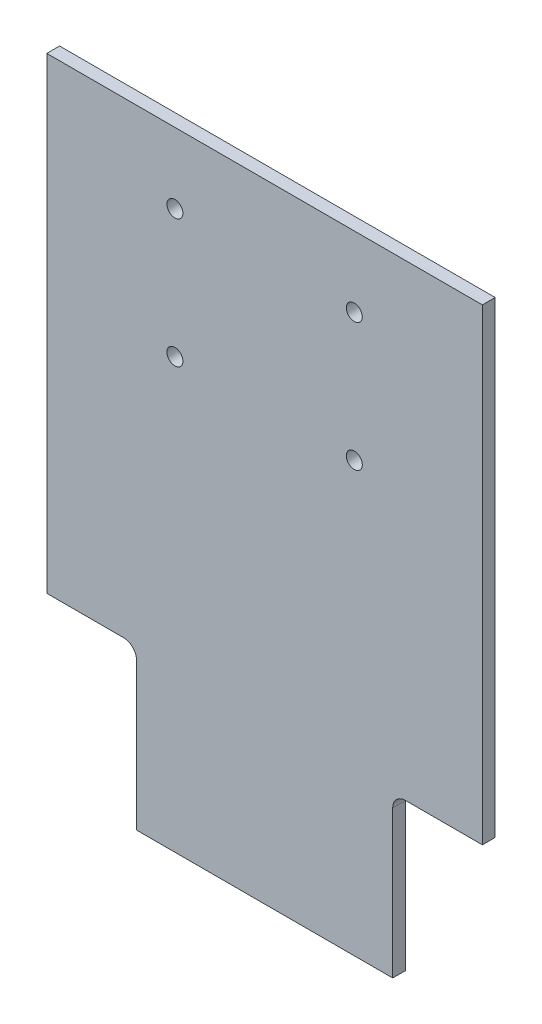
SolidWorks part; units mm, degrees
material "6063-T5"
ref_plane "前视基准面" through (0, 0, 0) normal (0, 0, 1) x (1, 0, 0)
ref_plane "上视基准面" through (0, 0, 0) normal (0, 1, 0) x (1, 0, 0)
ref_plane "右视基准面" through (0, 0, 0) normal (1, 0, 0) x (0, 0, -1)
sketch "草图1" plane through (0, 0, 0) normal (0, 0, 1) x (1, 0, 0)
  line L0 (34, 58) -> (34, 0) construction
  line L1 (0, 0) -> (68, 0)
  line L2 (0, 0) -> (0, 58)
  line L3 (0, 58) -> (68, 58)
  line L4 (68, 0) -> (68, 58)
  circle A0 centre (48, 27) radius 1.25
  circle A1 centre (20, 27) radius 1.25
  circle A2 centre (48, 47) radius 1.25
  circle A3 centre (20, 47) radius 1.25
  dimension "D3" = 2.5
  dimension "D4" = 28
  dimension "D5" = 27
  dimension "D7" = 20
  dimension "D8" = 2.5
  dimension "D1" = 68
  dimension "D2" = 58
extrude "凸台-拉伸1" add sketch "草图1" along normal blind 2
cosmetic thread "装饰螺纹线1" parameters "D2"=5
cosmetic thread "装饰螺纹线2" parameters "D2"=5
cosmetic thread "装饰螺纹线3" parameters "D2"=4
cosmetic thread "装饰螺纹线4" parameters "D2"=4
sketch "草图2" plane through (68, 0, 0) normal (1, 0, 0) x (0, 0, -1)
  line L0 (0, 0) -> (0, -40)
  line L1 (0, -40) -> (-2, -40)
  line L2 (-2, -40) -> (-2, 0)
  line L5 (0, 0) -> (0, 58) construction
  line L6 (-2, 0) -> (-2, 58) construction
  line L7 (0, 0) -> (-2, 0)
  dimension "D1" = 180
  dimension "D2" = 180
  dimension "D3" = 40
extrude "凸台-拉伸2" add sketch "草图2" against normal up to surface (68 mm away) up to face at (0, 29, 1)
sketch "草图3" plane through (0, 0, 2) normal (0, 0, 1) x (1, 0, 0)
  line L0 (14, -40) -> (54, -40) construction
  line L1 (0, -40) -> (68, -40) construction
  line L2 (54, -40) -> (54, -15)
  line L3 (54, -15) -> (68, -15)
  line L4 (68, -40) -> (68, 58) construction
  line L5 (68, -15) -> (68, -40)
  line L6 (68, -40) -> (54, -40)
  line L7 (14, -40) -> (14, -15)
  line L8 (14, -15) -> (0, -15)
  line L9 (0, 58) -> (0, -40) construction
  line L10 (0, -15) -> (0, -40)
  line L11 (0, -40) -> (14, -40)
  point P5 (34, -40)
  dimension "D1" = 40
  dimension "D2" = 14
  dimension "D3" = 25
  dimension "D4" = 25
extrude "切除-拉伸1" cut sketch "草图3" against normal blind 10
fillet "圆角1" radius 2 2 edges at (54, -15, 1) (14, -15, 1)
